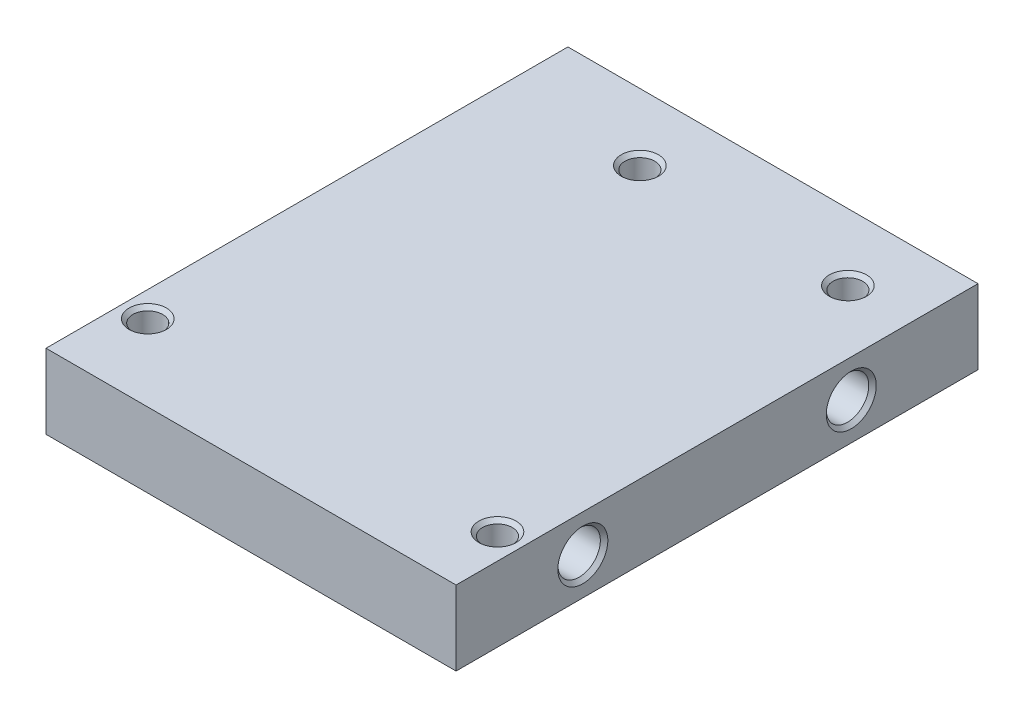
SolidWorks part; units mm, degrees
material "ABS PC"
ref_plane "Front Plane" through (0, 0, 0) normal (0, 0, 1) x (1, 0, 0)
ref_plane "Top Plane" through (0, 0, 0) normal (0, 1, 0) x (1, 0, 0)
ref_plane "Right Plane" through (0, 0, 0) normal (1, 0, 0) x (0, 0, -1)
sketch "Sketch1" plane through (0, 0, 0) normal (0, 1, 0) x (1, 0, 0)
  line L0 (-24.1, 26.05) -> (24.1, 26.05) construction
  line L1 (-27.5, 35) -> (27.5, 35)
  line L2 (-27.5, 35) -> (-27.5, -35)
  line L3 (-27.5, -35) -> (27.5, -35)
  line L4 (27.5, 35) -> (27.5, -35)
  line L5 (-27.5, 35) -> (27.5, -35) construction
  line L6 (-27.5, -35) -> (27.5, 35) construction
  line L7 (24.1, 26.05) -> (24.1, -26.05) construction
  line L8 (24.1, -26.05) -> (-24.1, -26.05) construction
  line L9 (-24.1, -26.05) -> (-24.1, 26.05) construction
  circle A0 centre (24.1, -26.05) radius 2
  circle A1 centre (-24.1, -24.75) radius 2
  circle A2 centre (19, 26.05) radius 2
  circle A3 centre (-8.9, 26.05) radius 2
  point P0 (0, 0)
  point P15 (24.1, 0)
  point P16 (0, -26.05)
  dimension "D5" = 4
  dimension "D1" = 70
  dimension "D2" = 55
  dimension "D3" = 52.1
  dimension "D4" = 48.2
  dimension "D6" = 1.3
  dimension "D7" = 5.1
  dimension "D8" = 33
extrude "Boss-Extrude1" add sketch "Sketch1" along normal mid plane 10
sketch "Sketch2" plane through (27.5, 0, 0) normal (1, 0, 0) x (0, 0, -1)
  line L0 (0, -1.812) -> (0, 3.1167) construction
  circle A0 centre (-18, 0) radius 2.85
  circle A1 centre (18, 0) radius 2.85
  dimension "D1" = 18
  dimension "D2" = 5.7
extrude "Cut-Extrude1" cut sketch "Sketch2" against normal blind 8
mirror "Mirror1" about plane through (0, 0, 0) normal (1, 0, 0) of "Cut-Extrude1"
chamfer "Chamfer1" distance 0.5 angle 45 8 edges at (-27.5, 0, -15.15) (-27.5, 0, 15.15) (27.5, 0, -15.15) (27.5, 0, 15.15) (-24.1, 5, 26.75) (24.1, 5, 28.05) (19, 5, -24.05) (-8.9, 5, -24.05)
